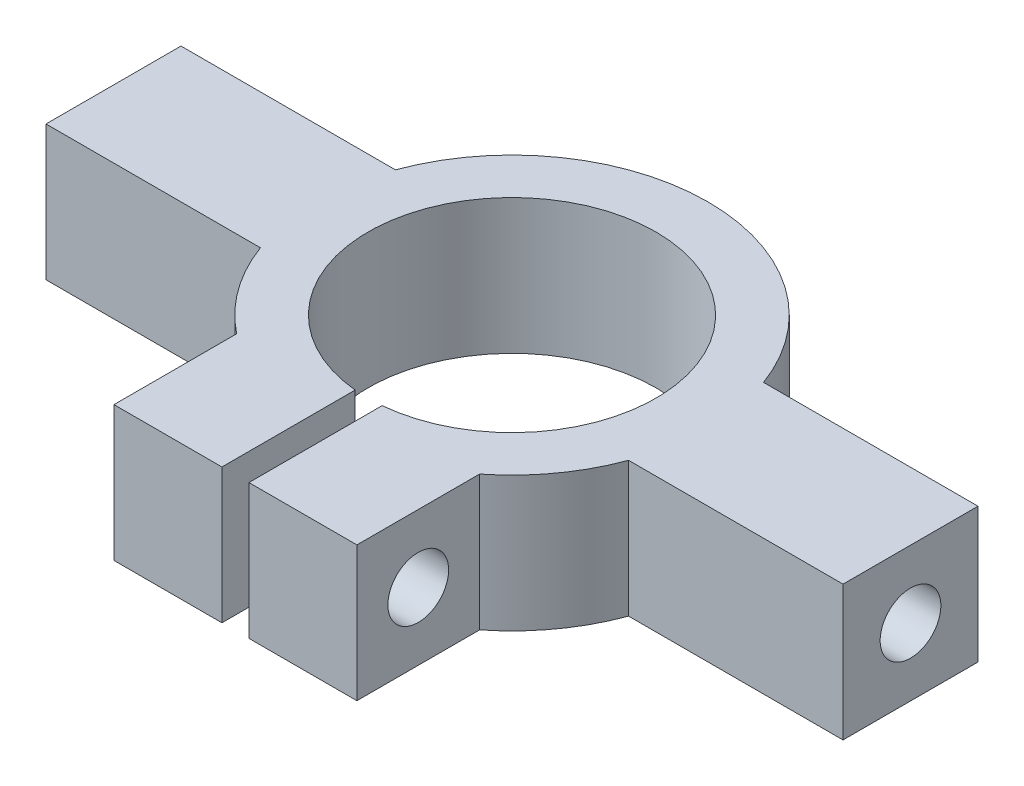
SolidWorks part; units mm, degrees
material "ABS"
ref_plane "Alzado" through (0, 0, 0) normal (0, 0, 1) x (1, 0, 0)
ref_plane "Planta" through (0, 0, 0) normal (0, 1, 0) x (1, 0, 0)
ref_plane "Vista lateral" through (0, 0, 0) normal (1, 0, 0) x (0, 0, -1)
sketch "Croquis1" plane through (0, 0, 0) normal (0, 1, 0) x (1, 0, 0)
  line L0 (0, 0) -> (0, -30) construction
  line L1 (30, 0) -> (-30, 0)
  line L2 (-30, 0) -> (-30, -10)
  line L3 (-30, -10) -> (-5, -10)
  line L4 (-5, -10) -> (-5, -16.3627)
  line L5 (30, 0) -> (30, -10)
  line L6 (30, -10) -> (5, -10)
  line L7 (5, -10) -> (5, -16.3627)
  arc A0 (-5, -16.3627) -> (5, -16.3627) centre (0, -30) ccw
  circle A1 centre (0, -30) radius 10.668
  point P7 (0, 0)
  dimension "D1" = 29.05
  dimension "D2" = 21.336
  dimension "D3" = 10
  dimension "D4" = 60
  dimension "D5" = 30
  dimension "D6" = 5
  dimension "D7" = 10
extrude "Saliente-Extruir1" add sketch "Croquis1" along normal mid plane 10
sketch "Croquis2" plane through (0, 0, 0) normal (0, 0, -1) x (-1, 0, 0)
  line L0 (-30, 0) -> (-25, 0) construction
  line L1 (-30, 5) -> (-30, -5) construction
  line L2 (-25, 0) -> (0, 0) construction
  line L3 (0, 0) -> (25, 0) construction
  line L4 (25, 0) -> (30, 0) construction
  line L5 (30, 5) -> (30, -5) construction
  circle A0 centre (25, 0) radius 2.25
  circle A1 centre (-25, 0) radius 2.25
  dimension "D2" = 4.5
  dimension "D1" = 5
extrude "Cortar-Extruir1" cut sketch "Croquis2" against normal up to next
sketch "Croquis3" plane through (0, 0, 0) normal (0, 1, 0) x (1, 0, 0)
  line L0 (-20, -10) -> (-14.0874, -33.5386)
  line L1 (-30, -10) -> (-5, -10) construction
  line L2 (-5, -10) -> (-5, -16.3627) construction
  line L3 (-20, -10) -> (-5, -10)
  line L4 (-5, -10) -> (-5, -16.3627)
  line L5 (0, -5.5) -> (0, 5.5) construction
  line L6 (20, -10) -> (5, -10)
  line L7 (20, -10) -> (14.0874, -33.5386)
  line L8 (5, -10) -> (5, -16.3627)
  arc A0 (-5, -16.3627) -> (5, -16.3627) centre (0, -30) ccw construction
  arc A1 (-5, -16.3627) -> (-14.0874, -33.5386) centre (0, -30) ccw
  arc A2 (5, -16.3627) -> (14.0874, -33.5386) centre (0, -30) cw
  dimension "D1" = 15
extrude "Saliente-Extruir2" add sketch "Croquis3" along normal mid plane 5 contours A1 L4 L3 L0 | L8 A2 L7 L6
ref_plane "Plano1" through (0, 0, 44.525) normal (0, 0, 1) x (1, 0, 0)
sketch "Croquis7" plane through (0, 5, 0) normal (0, 1, 0) x (1, 0, 0)
  line L0 (0, -40.668) -> (0, -44.525) construction
  line L2 (1, -46.5965) -> (-1, -46.5965)
  line L3 (1, -46.5965) -> (1, -38.5965)
  line L4 (1, -38.5965) -> (-1, -38.5965)
  line L5 (-1, -46.5965) -> (-1, -38.5965)
  line L6 (1, -46.5965) -> (-1, -38.5965) construction
  line L7 (1, -38.5965) -> (-1, -46.5965) construction
  circle A0 centre (0, -30) radius 10.668 construction
  arc A1 (-5, -16.3627) -> (5, -16.3627) centre (0, -30) ccw construction
  point P7 (0, -42.5965)
  dimension "D1" = 2
  dimension "D2" = 8
extrude "Cortar-Extruir5" cut sketch "Croquis7" against normal through all
sketch "Croquis8" plane through (0, 5, 0) normal (0, 1, 0) x (1, 0, 0)
  line L0 (-1, -44.4905) -> (-1, -50.4905)
  line L1 (-1, -50.4905) -> (-9, -50.4905)
  line L2 (-9, -50.4905) -> (-9, -41.4007)
  line L3 (0, -5.5) -> (0, 5.5) construction
  line L4 (9, -50.4905) -> (9, -41.4007)
  line L5 (1, -50.4905) -> (9, -50.4905)
  line L6 (1, -44.4905) -> (1, -50.4905)
  arc A0 (-5, -16.3627) -> (-1, -44.4905) centre (0, -30) ccw construction
  arc A1 (-9, -41.4007) -> (-1, -44.4905) centre (0, -30) ccw
  arc A2 (9, -41.4007) -> (1, -44.4905) centre (0, -30) cw
  dimension "D1" = 8
  dimension "D2" = 6
extrude "Saliente-Extruir3" add sketch "Croquis8" against normal up to surface (10 mm away) up to face at (0, -5, 18.7414)
sketch "Croquis9" plane through (9, 0, 0) normal (1, 0, 0) x (0, 0, -1)
  line L0 (-45.9456, 5) -> (-45.9456, -5) construction
  line L1 (-50.4905, 5) -> (-41.4007, 5) construction
  line L2 (-41.4007, -5) -> (-50.4905, -5) construction
  circle A0 centre (-45.9456, 0) radius 2.25
  dimension "D1" = 4.5
extrude "Cortar-Extruir6" cut sketch "Croquis9" against normal up to surface (18 mm away) up to face at (-9, 0, 45.9456)
sketch "Croquis10" plane through (0, 5, 0) normal (0, 1, 0) x (1, 0, 0)
  line L0 (5, -10) -> (5, -16.3627) construction
  line L1 (14.0874, -33.5386) -> (20, -10) construction
  line L2 (20, -10) -> (5, -10) construction
  line L3 (-5, -16.3627) -> (-5, -10) construction
  line L4 (-5, -10) -> (-20, -10) construction
  line L5 (-20, -10) -> (-14.0874, -33.5386) construction
  line L6 (5, -10) -> (5, -16.3627)
  line L7 (14.0874, -33.5386) -> (20, -10)
  line L8 (20, -10) -> (5, -10)
  line L9 (-5, -16.3627) -> (-5, -10)
  line L10 (-5, -10) -> (-20, -10)
  line L11 (-20, -10) -> (-14.0874, -33.5386)
  line L13 (-1, -50.4905) -> (-1, -40.621)
  line L14 (1, -40.621) -> (1, -50.4905)
  line L15 (1, -50.4905) -> (9, -50.4905)
  line L16 (9, -50.4905) -> (9, -41.4007)
  line L17 (5, -16.3627) -> (5, -10)
  line L18 (5, -10) -> (30, -10)
  line L19 (30, -10) -> (30, 0)
  line L20 (30, 0) -> (-30, 0)
  line L21 (-30, 0) -> (-30, -10)
  line L22 (-30, -10) -> (-5, -10)
  line L23 (-5, -10) -> (-5, -16.3627)
  line L24 (-9, -41.4007) -> (-9, -50.4905)
  line L25 (-9, -50.4905) -> (-1, -50.4905)
  line L26 (-1, -50.4905) -> (-1, -40.621)
  line L27 (1, -40.621) -> (1, -50.4905)
  line L28 (1, -50.4905) -> (9, -50.4905)
  line L29 (9, -50.4905) -> (9, -41.4007)
  line L30 (5, -16.3627) -> (5, -10)
  line L31 (5, -10) -> (30, -10)
  line L32 (30, -10) -> (30, 0)
  line L33 (30, 0) -> (-30, 0)
  line L34 (-30, 0) -> (-30, -10)
  line L35 (-30, -10) -> (-5, -10)
  line L36 (-5, -10) -> (-5, -16.3627)
  line L37 (-9, -41.4007) -> (-9, -50.4905)
  line L38 (-9, -50.4905) -> (-1, -50.4905)
  arc A0 (14.0874, -33.5386) -> (5, -16.3627) centre (0, -30) ccw construction
  arc A1 (-5, -16.3627) -> (-14.0874, -33.5386) centre (0, -30) ccw construction
  arc A2 (14.0874, -33.5386) -> (5, -16.3627) centre (0, -30) ccw
  arc A3 (1, -40.621) -> (-1, -40.621) centre (0, -30) ccw
  arc A4 (9, -41.4007) -> (5, -16.3627) centre (0, -30) ccw
  arc A5 (-5, -16.3627) -> (-9, -41.4007) centre (0, -30) ccw
  arc A6 (1, -40.621) -> (-1, -40.621) centre (0, -30) ccw
  arc A7 (9, -41.4007) -> (5, -16.3627) centre (0, -30) ccw
  arc A8 (-5, -16.3627) -> (-9, -41.4007) centre (0, -30) ccw
  arc A9 (-5, -16.3627) -> (-14.0874, -33.5386) centre (0, -30) ccw
  arc A10 (-5, -16.3627) -> (5, -16.3627) centre (0, -30) cw
  arc M22 (9, -41.4007) -> (5, -16.3627) centre (0, -30) ccw
  line M23 (5, -16.3627) -> (5, -10)
  line M24 (5, -10) -> (30, -10)
  line M25 (30, -10) -> (30, 0)
  line M26 (30, 0) -> (-30, 0)
  line M27 (-30, 0) -> (-30, -10)
  line M28 (-30, -10) -> (-5, -10)
  line M29 (-5, -10) -> (-5, -16.3627)
  arc M30 (-5, -16.3627) -> (-9, -41.4007) centre (0, -30) ccw
  dimension "D1" = 0
extrude "Cortar-Extruir7" cut sketch "Croquis10" against normal through all contours A10 M29 M23 M24 M25 M26 M27 M28 | L11 M28 M30 M29 | L7 M22 M24 M23
sketch "Croquis11" plane through (0, 5, 0) normal (0, 1, 0) x (1, 0, 0)
  line L0 (14.525, -30) -> (29.525, -30) construction
  line L1 (29.525, -35) -> (29.525, -25)
  line L2 (29.525, -25) -> (13.6373, -25)
  line L3 (29.525, -35) -> (13.6373, -35)
  line L4 (0, -5.5) -> (0, 5.5) construction
  line L5 (-29.525, -35) -> (-13.6373, -35)
  line L6 (-29.525, -35) -> (-29.525, -25)
  line L7 (-29.525, -25) -> (-13.6373, -25)
  arc A0 (9, -41.4007) -> (-9, -41.4007) centre (0, -30) ccw construction
  arc A1 (13.6373, -35) -> (13.6373, -25) centre (0, -30) ccw
  arc A2 (-13.6373, -35) -> (-13.6373, -25) centre (0, -30) cw
  point P9 (29.525, -30)
  dimension "D1" = 10
  dimension "D2" = 15
extrude "Saliente-Extruir4" add sketch "Croquis11" against normal up to surface (10 mm away)
sketch "Croquis12" plane through (29.525, 0, 0) normal (1, 0, 0) x (0, 0, -1)
  line L0 (-30, 5) -> (-30, -5) construction
  line L1 (-35, 5) -> (-25, 5) construction
  line L2 (-25, -5) -> (-35, -5) construction
  circle A0 centre (-30, 0) radius 2.25
  dimension "D1" = 4.5
extrude "Cortar-Extruir8" cut sketch "Croquis12" against normal blind 10
mirror "Simetría1" about plane through (0, 0, 0) normal (1, 0, 0) of "Cortar-Extruir8"
